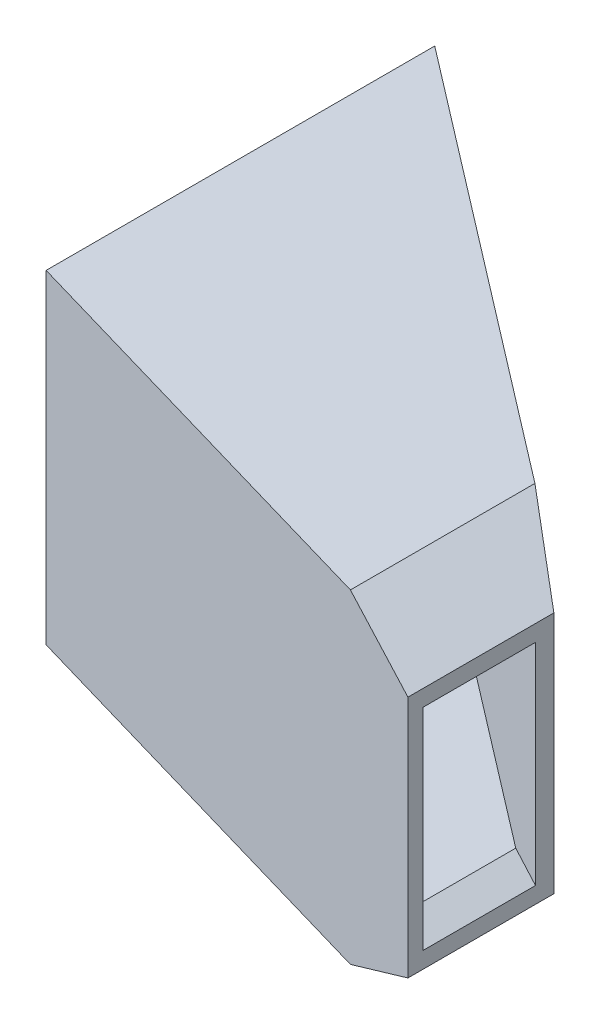
SolidWorks part; units mm, degrees
ref_plane "Front Plane" through (0, 0, 0) normal (0, 0, 1) x (1, 0, 0)
ref_plane "Top Plane" through (0, 0, 0) normal (0, 1, 0) x (1, 0, 0)
ref_plane "Right Plane" through (0, 0, 0) normal (1, 0, 0) x (0, 0, -1)
sketch "Sketch2" plane through (0, 0, 0) normal (0, 1, 0) x (1, 0, 0)
  line L0 (13.4282, -6.1) -> (13.4282, 41.83)
  line L8 (13.4282, 41.83) -> (76.3274, -6.3739)
  line L9 (76.3274, -6.3739) -> (76.3274, -24.3739)
  line L10 (76.3274, -24.3739) -> (13.4282, -6.1)
  dimension "D1" = 47.93
  dimension "D2" = 18
  dimension "D3" = 65.5
  dimension "D4" = 106.2
  dimension "D5" = 13.4282
  dimension "D6" = 41.83
extrude "Boss-Extrude1" add sketch "Sketch2" along normal blind 40
chamfer "Chamfer1" distance 5 distance2 10 1 edges at (76.3274, 40, 15.3739)
chamfer "Chamfer2" distance 10 distance2 5 1 edges at (76.3274, 0, 15.3739)
shell "Shell1" thickness 1.8
